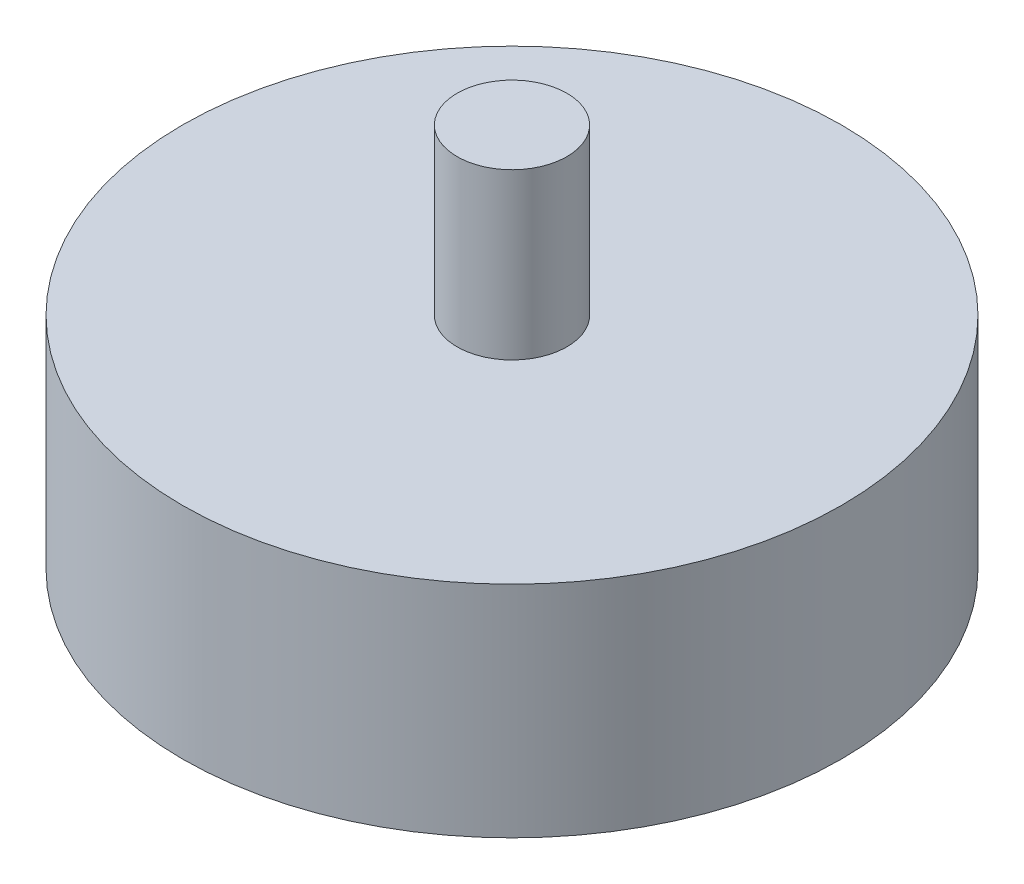
SolidWorks part; units mm, degrees
ref_plane "Front Plane" through (0, 0, 0) normal (0, 0, 1) x (1, 0, 0)
ref_plane "Top Plane" through (0, 0, 0) normal (0, 1, 0) x (1, 0, 0)
ref_plane "Right Plane" through (0, 0, 0) normal (1, 0, 0) x (0, 0, -1)
sketch "Sketch1" plane through (0, 0, 0) normal (0, 1, 0) x (1, 0, 0)
  circle A0 centre (0, 0) radius 5
  dimension "D1" = 10
extrude "Boss-Extrude1" add sketch "Sketch1" along normal blind 45
sketch "Sketch2" plane through (0, 0, 0) normal (0, 1, 0) x (1, 0, 0)
  circle A0 centre (0, 0) radius 30
  dimension "D1" = 60
extrude "Boss-Extrude2" add sketch "Sketch2" along normal blind 20 from offset 10
